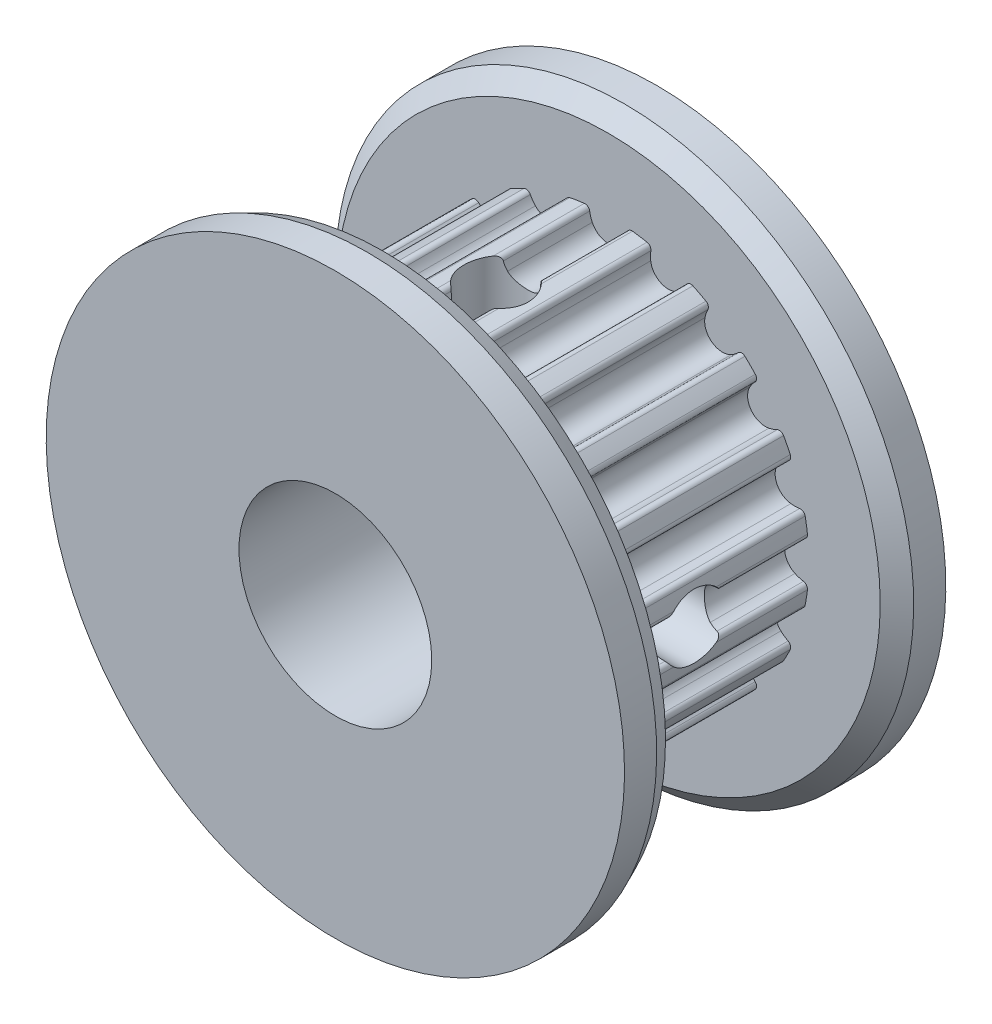
SolidWorks part; units mm, degrees
material "Aleación 6061"
ref_plane "Alzado" through (0, 0, 0) normal (0, 0, 1) x (1, 0, 0)
ref_plane "Planta" through (0, 0, 0) normal (0, 1, 0) x (1, 0, 0)
ref_plane "Vista lateral" through (0, 0, 0) normal (1, 0, 0) x (0, 0, -1)
sketch "Croquis1" plane through (0, 0, 0) normal (0, 0, 1) x (1, 0, 0)
  circle A0 centre (0, 0) radius 6.366
  dimension "D1" = 12.732
extrude "Saliente-Extruir1" add sketch "Croquis1" along normal blind 7
sketch "Croquis3" plane through (0, 0, 0) normal (0, 0, -1) x (-1, 0, 0)
  line L0 (0, 0) -> (0, 6.239) construction
  line L1 (0, 0) -> (0.976, 6.1622) construction
  line L2 (0.976, 6.1622) -> (0, 0) construction
  line L3 (0, 0) -> (-0.976, 6.1622) construction
  line L6 (0.976, 6.1622) -> (0.9959, 6.2876)
  line L8 (-0.976, 6.1622) -> (-0.9959, 6.2876)
  arc A0 (-0.7498, 6.1938) -> (-0.976, 6.1622) centre (0, 0) ccw
  arc A1 (-0.5037, 5.8059) -> (0.5037, 5.8059) centre (0, 6.039) ccw
  arc A2 (-0.5837, 6.0685) -> (-0.5037, 5.8059) centre (0.4038, 6.2259) ccw
  arc A3 (-0.5837, 6.0685) -> (-0.7498, 6.1938) centre (-0.7318, 6.0449) ccw
  arc A4 (0.5837, 6.0685) -> (0.5037, 5.8059) centre (-0.4038, 6.2259) cw
  arc A5 (0.5837, 6.0685) -> (0.7498, 6.1938) centre (0.7318, 6.0449) cw
  arc A6 (0.7498, 6.1938) -> (0.976, 6.1622) centre (0, 0) cw
  circle A7 centre (0, 0) radius 6.366 construction
  circle A11 centre (0, 0) radius 6.366
  circle M8 centre (0, 0) radius 6.366
  dimension "D1" = 6.239
  dimension "D4" = 1.11
  dimension "D5" = 2
  dimension "D7" = 0.3
  dimension "D3" = 18
  dimension "D6" = 0.2
extrude "Cortar-Extruir1" cut sketch "Croquis3" against normal through all contours A5 A6 L6 L8 A0 A3 A2 A1 A4 M8
pattern_circular "MatrizC1" count 20 over 360 about axis through (0, 0, 0) along (0, 0, 1) of "Cortar-Extruir1"
sketch "Croquis5" plane through (0, 0, 0) normal (1, 0, 0) x (0, 0, -1)
  line L0 (0, 0) -> (1.5, 0)
  line L1 (0, -0.5037) -> (0, 0.5037) construction
  line L2 (1.5, 0) -> (1.5, 9)
  line L4 (0, 8.4583) -> (0, 0)
  line L5 (-7, 0) -> (-8.5, 0)
  line L6 (-7, 0.5037) -> (-7, -0.5037) construction
  line L7 (-8.5, 0) -> (-8.5, 9)
  line L10 (-7, 0) -> (-7, 8.776)
  line L11 (-8.5, 9) -> (-7.5, 9)
  line L12 (-7.5, 9) -> (-7, 8.776)
  line L13 (1.5, 9) -> (0.5, 9)
  line L14 (0.5, 9) -> (0, 8.4583)
  dimension "D1" = 9
  dimension "D2" = 1
  dimension "D3" = 9
  dimension "D4" = 0.5
  dimension "D5" = 1
  dimension "D6" = 0.5
revolve "Revolución1" add sketch "Croquis5" angle 360 about L5
sketch "Croquis6" plane through (0, 0, 8.5) normal (0, 0, 1) x (1, 0, 0)
  circle A0 centre (0, 0) radius 3
  dimension "D1" = 6
extrude "Cortar-Extruir2" cut sketch "Croquis6" against normal through all
sketch "Croquis7" plane through (0, 0, 0) normal (1, 0, 0) x (0, 0, -1)
  circle A0 centre (-3.5, 0) radius 1
  dimension "D1" = 2
extrude "Cortar-Extruir3" cut sketch "Croquis7" against normal through all both and the other way through all
sketch "Croquis8" plane through (0, 0, 0) normal (0, 1, 0) x (1, 0, 0)
  line L0 (0, 1.5) -> (0, -8.5) construction
  line L1 (9, 1.5) -> (-9, 1.5) construction
  line L2 (-3, -8.5) -> (3, -8.5) construction
  circle A1 centre (0, -3.5) radius 1
  dimension "D1" = 2
extrude "Cortar-Extruir4" cut sketch "Croquis8" against normal through all both and the other way through all
